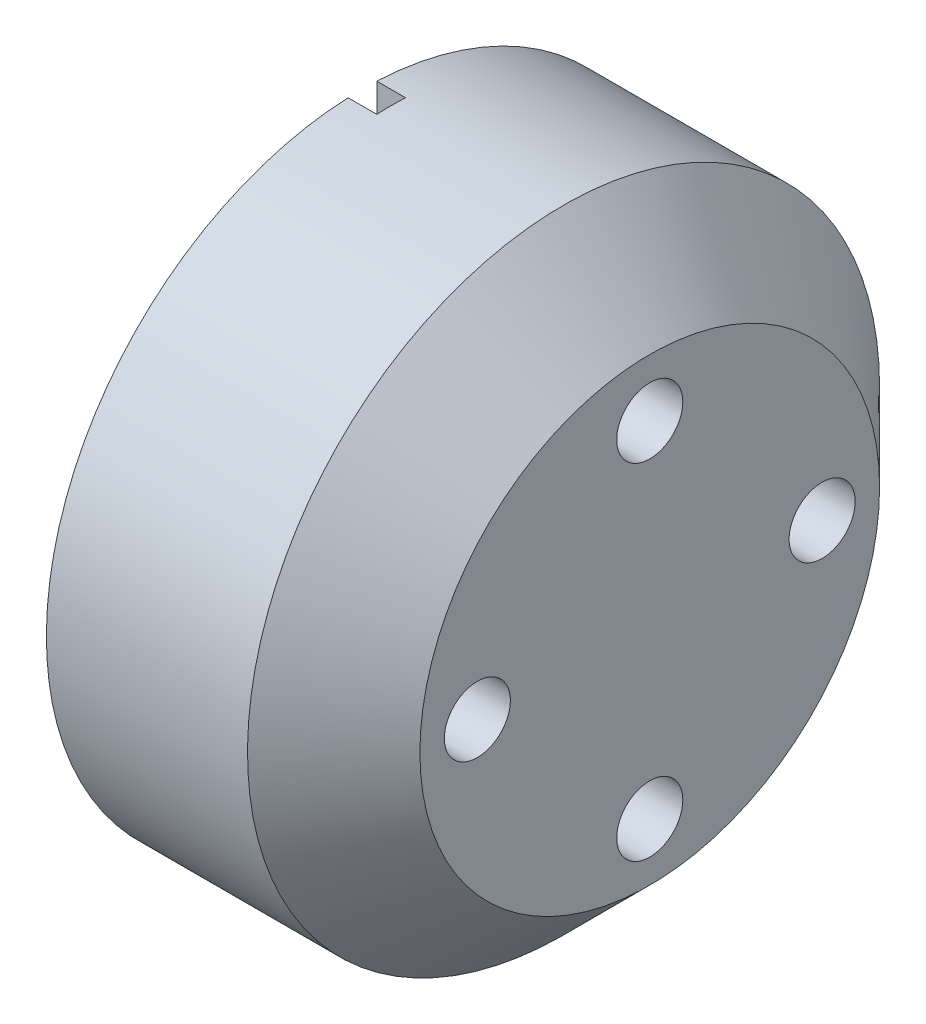
SolidWorks part; units mm, degrees
ref_plane "Front Plane" through (0, 0, 0) normal (0, 0, 1) x (1, 0, 0)
ref_plane "Top Plane" through (0, 0, 0) normal (0, 1, 0) x (1, 0, 0)
ref_plane "Right Plane" through (0, 0, 0) normal (1, 0, 0) x (0, 0, -1)
sketch "Sketch2" plane through (0, 0, 0) normal (1, 0, 0) x (0, 0, -1)
  circle A0 centre (0, 0) radius 11
  circle A1 centre (0, 0) radius 6 construction
  circle A2 centre (0, 6) radius 1.15
  circle A3 centre (-6, 0) radius 1.15
  circle A4 centre (0, -6) radius 1.15
  circle A5 centre (6, 0) radius 1.15
  dimension "D1" = 12
  dimension "D2" = 22
  dimension "D3" = 2.3
extrude "Boss-Extrude1" add sketch "Sketch2" along normal blind 10
chamfer "Chamfer1" distance 3 1 edges at (10, 0, -11)
sketch "Sketch5" plane through (0, 0, 0) normal (-1, 0, 0) x (0, 0, 1)
  circle A0 centre (-6, 0) radius 2
  circle A1 centre (0, 6) radius 2
  circle A2 centre (0, -6) radius 2
  circle A3 centre (6, 0) radius 2
  dimension "D1" = 4
extrude "Cut-Extrude2" cut sketch "Sketch5" against normal offset from surface (4.5 mm away) 5.5 up to face at (10, 0, -8)
sketch "Sketch6" plane through (0, 0, 0) normal (-1, 0, 0) x (0, 0, 1)
  line L0 (-5.3033, -5.3033) -> (5.3033, 5.3033) construction
  line L1 (-5.3033, 5.3033) -> (5.3033, -5.3033) construction
  line L2 (0, 7.5) -> (0, 0) construction
  circle A0 centre (0, 0) radius 7.5 construction
  circle A1 centre (5.3033, 5.3033) radius 2
  circle A2 centre (-5.3033, 5.3033) radius 2
  circle A3 centre (-5.3033, -5.3033) radius 2
  circle A4 centre (5.3033, -5.3033) radius 2
  dimension "D1" = 15
  dimension "D3" = 4
  dimension "D2" = 45
extrude "Cut-Extrude3" cut sketch "Sketch6" against normal blind 8
chamfer "Chamfer2" distance 0.3 distance2 1.2 4 edges at (0, -5.3033, -3.3033) (0, -5.3033, 7.3033) (0, 5.3033, 7.3033) (0, 5.3033, -3.3033)
sketch "Sketch7" plane through (0, 0, 0) normal (-1, 0, 0) x (0, 0, 1)
  line L0 (0, 0) -> (0, 11) construction
  line L2 (-0.5, 9.5) -> (0.5, 9.5)
  line L3 (-0.5, 9.5) -> (-0.5, 13.3295)
  line L4 (-0.5, 13.3295) -> (0.5, 13.3295)
  line L5 (0.5, 9.5) -> (0.5, 13.3295)
  line L6 (-0.5, 9.5) -> (0.5, 13.3295) construction
  line L7 (-0.5, 13.3295) -> (0.5, 9.5) construction
  circle A0 centre (0, 0) radius 11 construction
  point P6 (0, 11.4147)
  dimension "D2" = 9.5
  dimension "D1" = 1
extrude "Cut-Extrude4" cut sketch "Sketch7" against normal blind 1
